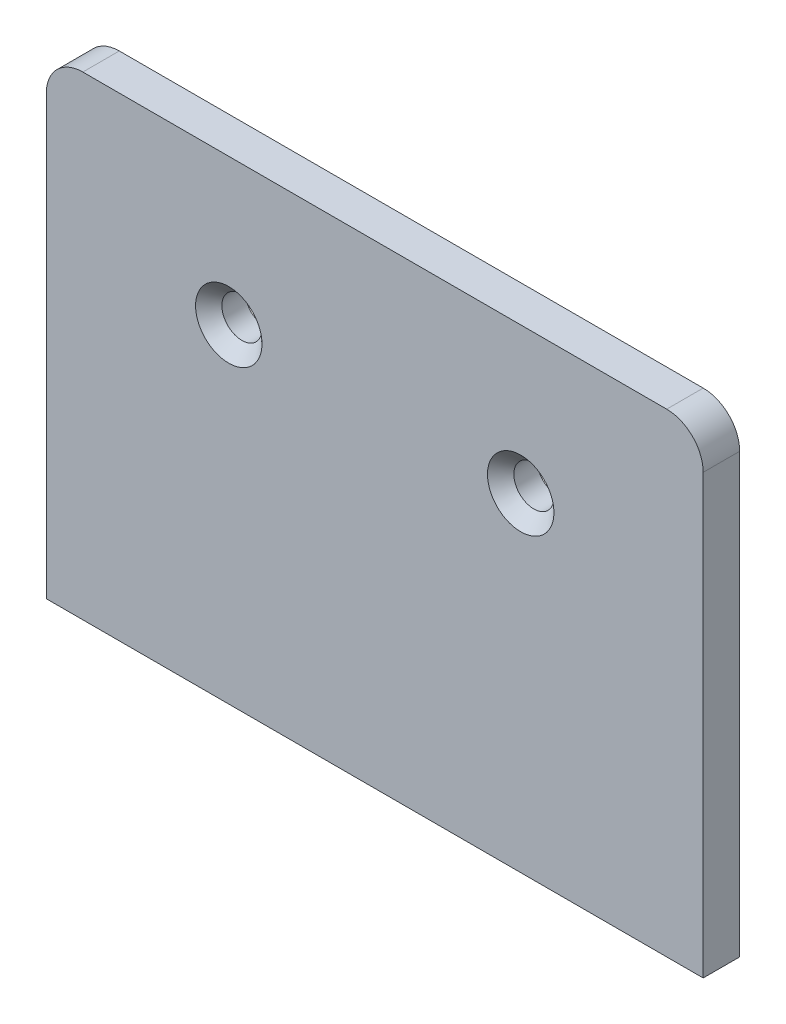
SolidWorks part; units mm, degrees
ref_plane "前视基准面" through (0, 0, 0) normal (0, 0, 1) x (1, 0, 0)
ref_plane "上视基准面" through (0, 0, 0) normal (0, 1, 0) x (1, 0, 0)
ref_plane "右视基准面" through (0, 0, 0) normal (1, 0, 0) x (0, 0, -1)
ref_plane "基准面1" through (0, 0, 0) normal (0, 0, -1) x (-1, 0, 0)
sketch "草图1" plane through (0, 0, 0) normal (0, 0, -1) x (-1, 0, 0)
  line L0 (45, 40) -> (45, 105)
  line L1 (45, 105) -> (-45, 105)
  line L2 (-45, 105) -> (-45, 40)
  line L3 (-45, 40) -> (45, 40)
extrude "凸台-拉伸1" add sketch "草图1" against normal blind 5
hole_wizard "孔1" positions "草图3" profile "草图2" legacy
sketch "草图3" plane through (0, 0, 5) normal (0, 0, 1) x (1, 0, 0)
  point P0 (-20, 85)
sketch "草图2" plane through (-20, 85, 5) normal (1, 0, 0) x (0, -1, 0)
  line L0 (0, 0) -> (0, 5)
  line L1 (0, 5) -> (2.75, 5)
  line L2 (2.75, 5) -> (2.75, 0)
  line L3 (2.75, 0) -> (0, 0)
  line L4 (0, 110) -> (0, -10) construction
  dimension "直径" = 5.5
  dimension "深度" = 5
hole_wizard "孔2" positions "草图5" profile "草图4" legacy
sketch "草图5" plane through (0, 0, 5) normal (0, 0, 1) x (1, 0, 0)
  point P0 (20, 85)
sketch "草图4" plane through (20, 85, 5) normal (1, 0, 0) x (0, -1, 0)
  line L0 (0, 0) -> (0, 5)
  line L1 (0, 5) -> (2.75, 5)
  line L2 (2.75, 5) -> (2.75, 0)
  line L3 (2.75, 0) -> (0, 0)
  line L4 (0, 110) -> (0, -10) construction
  dimension "直径" = 5.5
  dimension "深度" = 5
chamfer "倒角1" distance 1.8021 angle 45 1 edges at (-17.25, 85, 5)
chamfer "倒角2" distance 1.8021 angle 45 1 edges at (22.75, 85, 5)
fillet "圆角1" radius 5 1 edges at (45, 105, 2.5)
fillet "圆角2" radius 5 1 edges at (-45, 105, 2.5)
